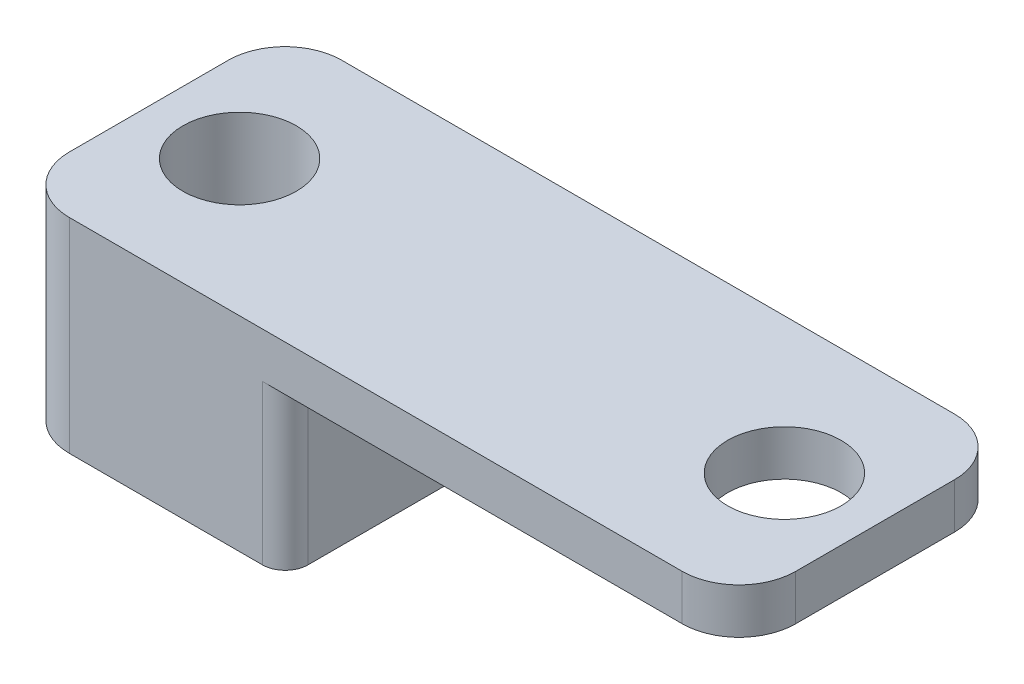
SolidWorks part; units mm, degrees
ref_plane "Front" through (0, 0, 0) normal (0, 0, 1) x (1, 0, 0)
ref_plane "Top" through (0, 0, 0) normal (0, 1, 0) x (1, 0, 0)
ref_plane "Right" through (0, 0, 0) normal (1, 0, 0) x (0, 0, -1)
sketch "Эскиз1" plane through (0, 0, 0) normal (0, 1, 0) x (1, 0, 0)
  line L0 (-12, 0) -> (12, 0) construction
  line L1 (-13.5, 6) -> (13.5, 6)
  line L2 (-16, 3.5) -> (-16, -3.5)
  line L3 (-13.5, -6) -> (13.5, -6)
  line L4 (16, 3.5) -> (16, -3.5)
  line L5 (-16, 6) -> (16, -6) construction
  line L6 (-16, -6) -> (16, 6) construction
  circle A0 centre (-12, 0) radius 2.5
  circle A1 centre (12, 0) radius 2.5
  arc A2 (13.5, 6) -> (16, 3.5) centre (13.5, 3.5) cw
  arc A3 (13.5, -6) -> (16, -3.5) centre (13.5, -3.5) ccw
  arc A4 (-16, -3.5) -> (-13.5, -6) centre (-13.5, -3.5) ccw
  arc A5 (-13.5, 6) -> (-16, 3.5) centre (-13.5, 3.5) ccw
  point P0 (0, 0)
  dimension "D2" = 32
  dimension "D4" = 2.5
  dimension "D1" = 24
  dimension "D3" = 12
extrude "Бобышка-Вытянуть1" add sketch "Эскиз1" along normal blind 20
sketch "Эскиз2" plane through (0, 0, 0) normal (0, -1, 0) x (1, 0, 0)
  line L1 (24.6759, -10.1694) -> (-3.9899, -10.1694)
  line L2 (24.6759, -10.1694) -> (24.6759, 10.1694)
  line L3 (24.6759, 10.1694) -> (-3.9899, 10.1694)
  line L4 (-3.9899, -10.1694) -> (-3.9899, 10.1694)
  line L5 (24.6759, -10.1694) -> (-3.9899, 10.1694) construction
  line L6 (24.6759, 10.1694) -> (-3.9899, -10.1694) construction
extrude "Вырез-Вытянуть1" cut sketch "Эскиз2" against normal blind 18
sketch "Эскиз3" plane through (0, 0, 0) normal (0, -1, 0) x (1, 0, 0)
  line L1 (-16.3958, 7.5561) -> (4.8912, 7.5561)
  line L2 (-16.3958, 7.5561) -> (-16.3958, -7.6301)
  line L3 (-16.3958, -7.6301) -> (4.8912, -7.6301)
  line L4 (4.8912, 7.5561) -> (4.8912, -7.6301)
  line L5 (-16.3958, 7.5561) -> (4.8912, -7.6301) construction
  line L6 (-16.3958, -7.6301) -> (4.8912, 7.5561) construction
  point P0 (-5.7523, -0.037)
extrude "Вырез-Вытянуть2" cut sketch "Эскиз3" against normal blind 11
fillet "Скругление1" radius 1 2 edges at (-3.9899, 14.5, 6) (-3.9899, 14.5, -6)
